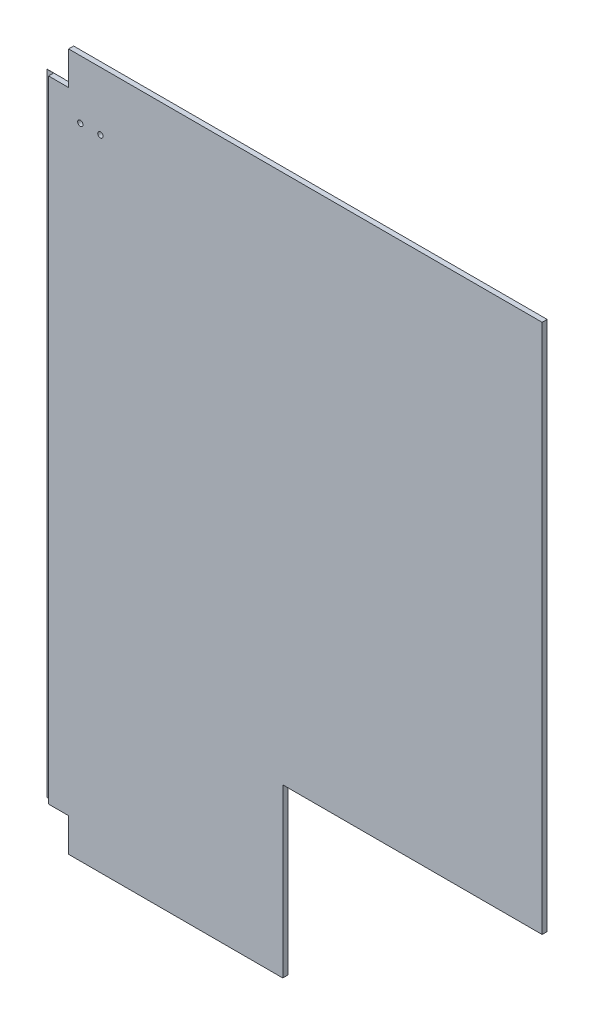
SolidWorks part; units mm, degrees
ref_plane "Front Plane" through (0, 0, 0) normal (0, 0, 1) x (1, 0, 0)
ref_plane "Top Plane" through (0, 0, 0) normal (0, 1, 0) x (1, 0, 0)
ref_plane "Right Plane" through (0, 0, 0) normal (1, 0, 0) x (0, 0, -1)
sketch "Sketch1" plane through (0, 0, 0) normal (0, 0, 1) x (1, 0, 0)
  line L1 (0, 0) -> (140, 0)
  line L2 (0, 0) -> (0, 416.9)
  line L3 (0, 416.9) -> (300, 416.9)
  line L4 (300, 100) -> (300, 416.9)
  line L7 (300, 100) -> (140, 100)
  line L8 (140, 0) -> (140, 100)
  dimension "D2" = 300
  dimension "D3" = 100
  dimension "D4" = 160
extrude "Boss-Extrude1" add sketch "Sketch1" along normal blind 3
sketch "Sketch2" plane through (0, 0, 0) normal (0, 0, 1) x (1, 0, 0)
  line L0 (0, 0) -> (140, 0) construction
  line L1 (6, 416.9) -> (-4, 416.9)
  line L2 (6, 416.9) -> (6, 0)
  line L3 (6, 0) -> (-4, 0)
  line L4 (-4, 416.9) -> (-4, 0)
  line L7 (300, 416.9) -> (0, 416.9) construction
  line L8 (0, 416.9) -> (0, 0) construction
  dimension "D1" = 10
  dimension "D2" = 4
extrude "Boss-Extrude2" add sketch "Sketch2" against normal blind 0.1 separate body
sketch "Sketch3" plane through (0, 0, 3) normal (0, 0, 1) x (1, 0, 0)
  line L0 (0, 416.9) -> (-4, 416.9)
  line L1 (0, 416.9) -> (12, 416.9)
  line L2 (0, 416.9) -> (0, 396.9) construction
  line L3 (0, 396.9) -> (12, 396.9)
  line L4 (12, 416.9) -> (12, 396.9)
  line L5 (0, 0) -> (12, 0)
  line L6 (0, 0) -> (0, 20) construction
  line L7 (0, 20) -> (12, 20)
  line L8 (12, 0) -> (12, 20)
  line L9 (-4, 416.9) -> (-4, 0) construction
  line L10 (-4, 416.9) -> (-4, 396.9)
  line L11 (-4, 396.9) -> (0, 396.9)
  line L12 (0, 416.9) -> (0, 396.9) construction
  line L13 (0, 20) -> (-4, 20)
  line L14 (-4, 20) -> (-4, 0)
  line L15 (-4, 0) -> (0, 0)
  dimension "D1" = 12
  dimension "D2" = 20
  dimension "D3" = 20
  dimension "D4" = 12
extrude "Cut-Extrude1" cut sketch "Sketch3" against normal blind 10
sketch "Sketch4" plane through (0, 0, 3) normal (0, 0, 1) x (1, 0, 0)
  line L0 (12, 381.9) -> (74.2849, 381.9) construction
  line L4 (300, 416.9) -> (12, 416.9) construction
  line L5 (12, 396.9) -> (12, 416.9) construction
  line L6 (0, 396.9) -> (0, 20) construction
  point P4 (19, 381.9)
  point P5 (31, 381.9)
  dimension "D1" = 31
  dimension "D2" = 12
  dimension "D3" = 35
hole_wizard "M3 Clearance Hole1" positions "Sketch4" profile "Sketch5" hole size "M3" standard "ANSI Metric" end condition through all
sketch "Sketch5" plane through (31, 381.9, 3) normal (1, 0, 0) x (0, -1, 0)
  line L0 (0, 0) -> (0, 3.1)
  line L1 (0, 3.1) -> (1.6, 3.1)
  line L2 (1.6, 3.1) -> (1.6, 0)
  line L5 (1.6, 0) -> (0, 0)
  line L11 (0, -6.35) -> (0, 107.95) construction
  dimension "Thru Hole Dia." = 3.2
  dimension "Thru Hole Depth" = 3.1
sketch "Sketch6" plane through (0, 0, 3) normal (0, 0, 1) x (1, 0, 0)
  line L0 (140, 100) -> (300, 100) construction
  line L1 (300, 416.9) -> (295, 416.9)
  line L2 (300, 416.9) -> (300, 100)
  line L3 (300, 100) -> (295, 100)
  line L4 (295, 416.9) -> (295, 100)
  dimension "D1" = 5
extrude "Cut-Extrude2" cut sketch "Sketch6" against normal blind 10
